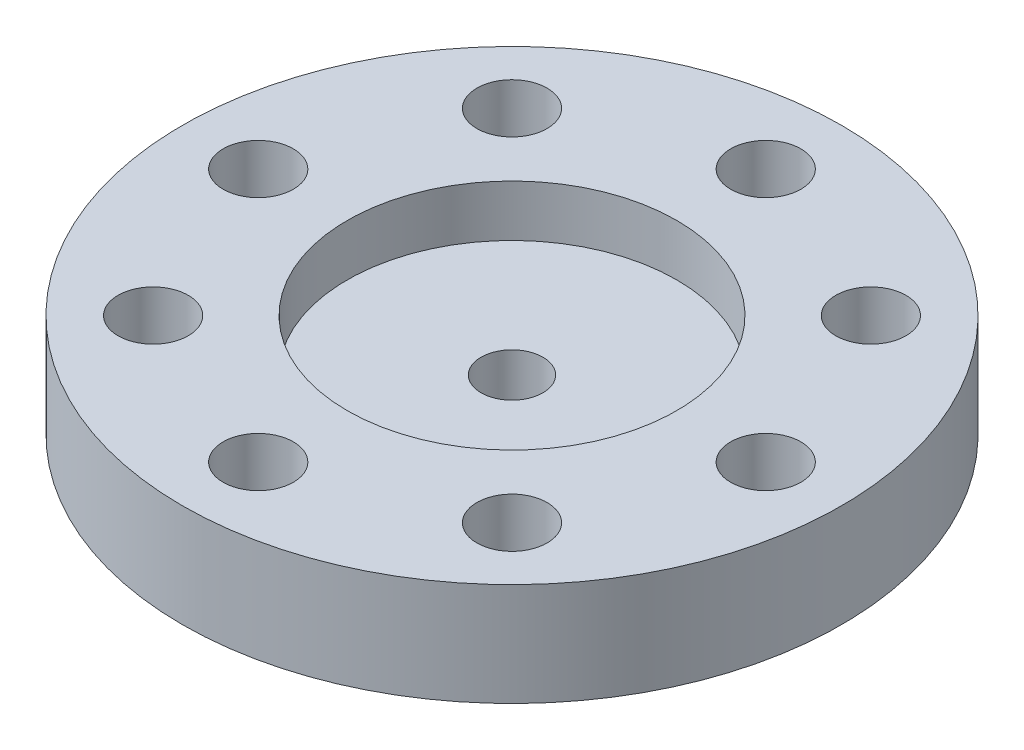
SolidWorks part; units mm, degrees
material "6061 Alloy"
ref_plane "Front Plane" through (0, 0, 0) normal (0, 0, 1) x (1, 0, 0)
ref_plane "Top Plane" through (0, 0, 0) normal (0, 1, 0) x (1, 0, 0)
ref_plane "Right Plane" through (0, 0, 0) normal (1, 0, 0) x (0, 0, -1)
sketch "Sketch1" plane through (0, 0, 0) normal (0, 0, 1) x (1, 0, 0)
  line L0 (-12.7, 0) -> (12.7, 0) construction
  line L1 (0, 0) -> (0, 4.7625) construction
  line L2 (-12.7, 4.7625) -> (-12.7, 0.7937)
  line L3 (-12.7, 0.7937) -> (-1.1906, 0.7937)
  line L4 (-1.1906, 0.7937) -> (-1.1906, 2.7781)
  line L5 (-1.1906, 2.7781) -> (-6.35, 2.7781)
  line L6 (-6.35, 2.7781) -> (-6.35, 4.7625)
  line L7 (-6.35, 4.7625) -> (-12.7, 4.7625)
  dimension "D1" = 25.4
  dimension "D2" = 9.525
  dimension "D3" = 1.5875
  dimension "D4" = 2.3813
  dimension "D5" = 12.7
revolve "Revolve1" add sketch "Sketch1" angle 360 about L1
hole_wizard "#6-32 Tapped Hole1" positions "Sketch3" profile "Sketch2" tap size "#6-32" standard "ANSI Inch" end condition through all
sketch "Sketch3" plane through (0, 4.7625, 0) normal (0, 1, 0) x (1, 0, 0)
  line L0 (-9.779, 0) -> (9.779, 0) construction
  point P0 (9.779, 0)
  dimension "D1" = 19.558
sketch "Sketch2" plane through (9.779, 4.7625, 0) normal (1, 0, 0) x (0, 0, 1)
  line L0 (0, 0) -> (0, 3.9687)
  line L1 (0, 3.9687) -> (1.3525, 3.9687)
  line L2 (1.3525, 3.9687) -> (1.3525, 0)
  line L5 (1.3525, 0) -> (0, 0)
  line L11 (0, -6.35) -> (0, 107.95) construction
  dimension "Thread Major Dia." = 2.7051
  dimension "Thru Tap Drill Depth" = 3.9687
pattern_circular "CirPattern1" count 8 over 360 about axis through (0, 0, 0) along (0, 1, 0) of "#6-32 Tapped Hole1"
